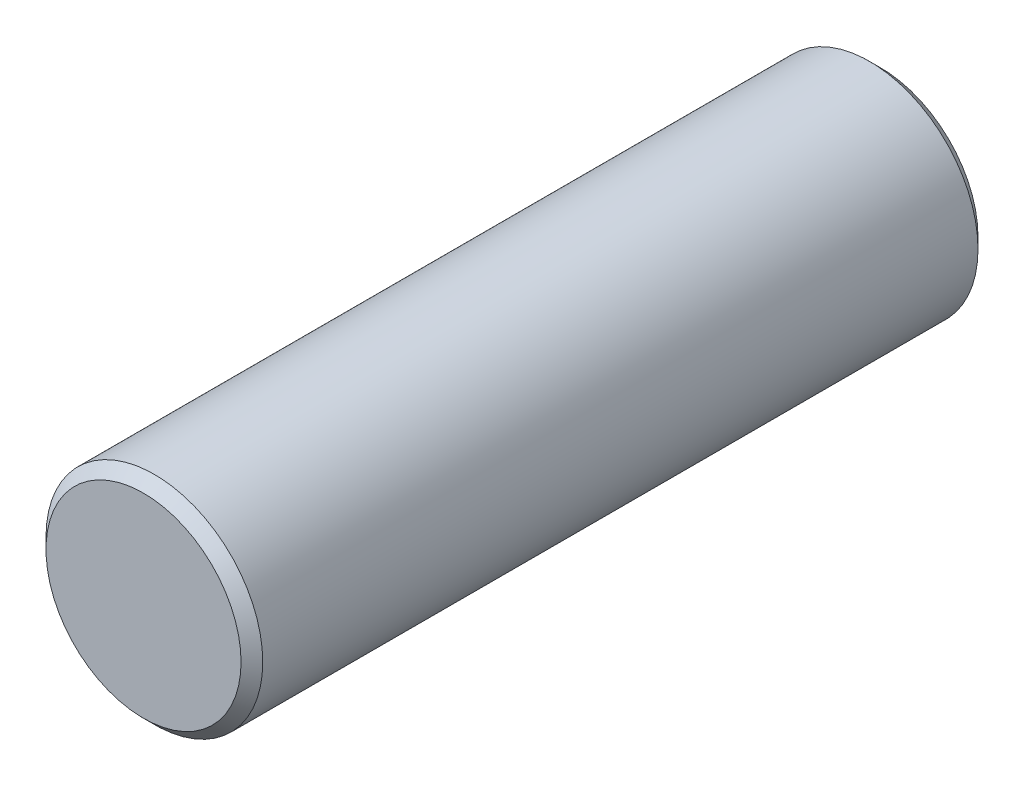
SolidWorks part; units mm, degrees
ref_plane "Front Plane" through (0, 0, 0) normal (0, 0, 1) x (1, 0, 0)
ref_plane "Top Plane" through (0, 0, 0) normal (0, 1, 0) x (1, 0, 0)
ref_plane "Right Plane" through (0, 0, 0) normal (1, 0, 0) x (0, 0, -1)
sketch "Sketch1" plane through (0, 0, 0) normal (0, 0, 1) x (1, 0, 0)
  circle A0 centre (0, 0) radius 5
  dimension "D1" = 10
extrude "Boss-Extrude1" add sketch "Sketch1" along normal mid plane 34
chamfer "Chamfer1" distance 0.5 angle 45 2 edges at (5, 0, -17) (5, 0, 17)
